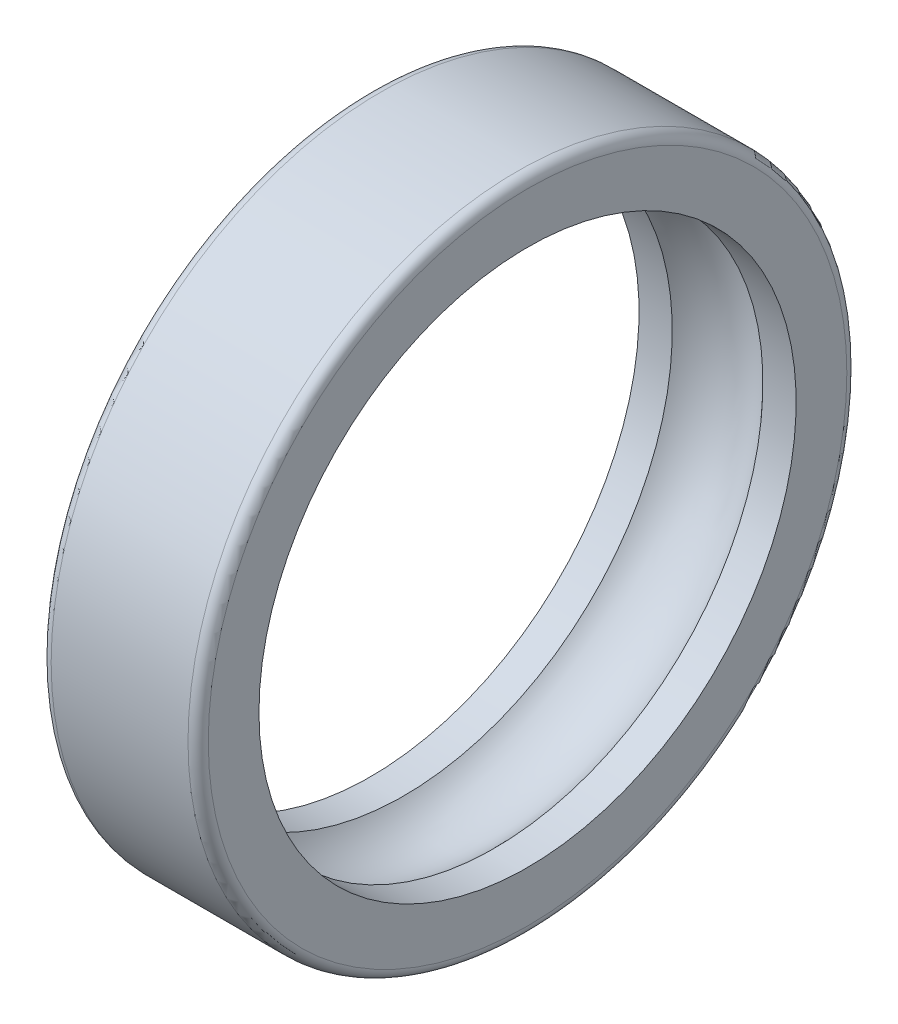
SolidWorks part; units mm, degrees
ref_plane "前视基准面" through (0, 0, 0) normal (0, 0, 1) x (1, 0, 0)
ref_plane "上视基准面" through (0, 0, 0) normal (0, 1, 0) x (1, 0, 0)
ref_plane "右视基准面" through (0, 0, 0) normal (1, 0, 0) x (0, 0, -1)
sketch "草图1" plane through (0, 0, 0) normal (0, 0, 1) x (1, 0, 0)
  line L0 (0, 0) -> (0, 59) construction
  line L1 (-15.5, 53) -> (-8.9443, 53)
  line L2 (-15.5, 65) -> (15.5, 65)
  line L3 (-15.5, 65) -> (-15.5, 53)
  line L5 (15.5, 65) -> (15.5, 53)
  line L6 (-15.5, 65) -> (15.5, 53) construction
  line L7 (-15.5, 53) -> (15.5, 65) construction
  line L8 (8.9443, 53) -> (15.5, 53)
  line L9 (0, 0) -> (12.6153, 0) construction
  arc A0 (-8.9443, 53) -> (8.9443, 53) centre (0, 45) cw
  dimension "D3" = 12
  dimension "D1" = 8
  dimension "D2" = 31
  dimension "D4" = 53
  dimension "D5" = 65
revolve "旋转1" add sketch "草图1" angle 360 about L9
fillet "圆角1" radius 2 2 edges at (15.5, 0, 65) (-15.5, 0, 65)
